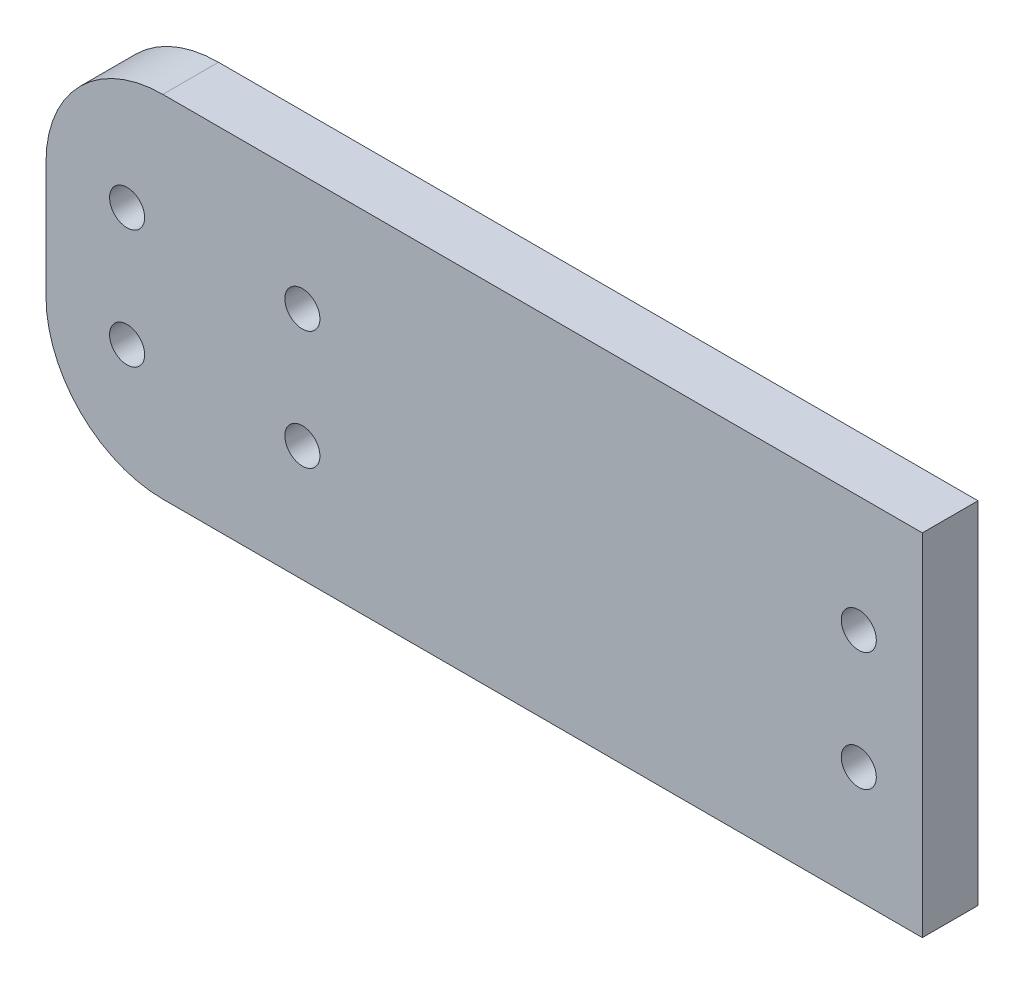
SolidWorks part; units mm, degrees
ref_plane "Front" through (0, 0, 0) normal (0, 0, 1) x (1, 0, 0)
ref_plane "Top" through (0, 0, 0) normal (0, 1, 0) x (1, 0, 0)
ref_plane "Right" through (0, 0, 0) normal (1, 0, 0) x (0, 0, -1)
sketch "Esquisse1" plane through (0, 0, 0) normal (0, 0, 1) x (1, 0, 0)
  line L1 (-37.5, 15) -> (37.5, 15)
  line L2 (-37.5, 15) -> (-37.5, -15)
  line L3 (-37.5, -15) -> (37.5, -15)
  line L4 (37.5, 15) -> (37.5, -15)
  line L5 (-37.5, 15) -> (37.5, -15) construction
  line L6 (-37.5, -15) -> (37.5, 15) construction
  point P0 (0, 0)
  dimension "D1" = 75
  dimension "D2" = 30
extrude "Boss.-Extru.1" add sketch "Esquisse1" along normal blind 4.7625
fillet "Congé1" radius 10 2 edges at (-37.5, -15, 2.3813) (-37.5, 15, 2.3813)
sketch "Esquisse3" plane through (0, 0, 4.7625) normal (0, 0, 1) x (1, 0, 0)
  line L5 (50, 0) -> (-50, 0) construction
  line L6 (37.5, 15) -> (-27.5, 15) construction
  line L7 (-37.5, 5) -> (-37.5, -5) construction
  circle A1 centre (-15.56, 5.08) radius 1.5
  circle A2 centre (-15.56, -5.08) radius 1.5
  circle A3 centre (32.06, -5.08) radius 1.5
  circle A4 centre (32.06, 5.08) radius 1.5
  circle A6 centre (-30.56, 5.08) radius 1.5
  circle A7 centre (-30.56, -5.08) radius 1.5
  dimension "D5" = 21.94
  dimension "D6" = 9.92
  dimension "D7" = 3
  dimension "D1" = 2
extrude "Enlèv. mat.-Extru.3" cut sketch "Esquisse3" against normal blind 10
